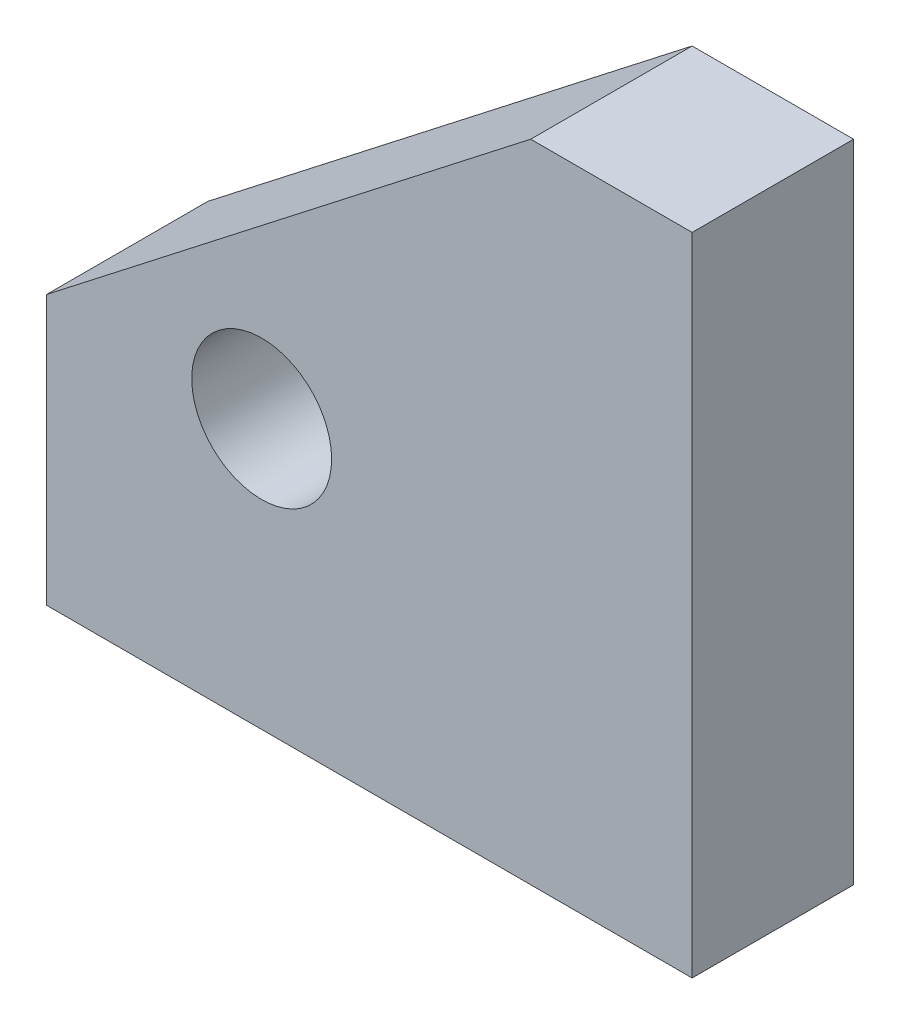
SolidWorks part; units mm, degrees
ref_plane "Front Plane" through (0, 0, 0) normal (1, 0, 0) x (0, 1, 0)
ref_plane "Top Plane" through (0, 0, 0) normal (0, 0, 1) x (0, 1, 0)
ref_plane "Right Plane" through (0, 0, 0) normal (0, 1, 0) x (-1, 0, 0)
sketch "Sketch1" plane through (0, 0, 0) normal (0, 0, 1) x (0, 1, 0)
  line L0 (0, 0) -> (0, 60)
  line L1 (0, 60) -> (60, 60)
  line L2 (60, 60) -> (60, 0)
  line L3 (60, 0) -> (0, 0)
  line L5 (25, 60) -> (60, 15)
  circle A0 centre (25, 40) radius 6.5
  dimension "D3" = 13
  dimension "D1" = 60
  dimension "D2" = 60
  dimension "D4" = 40
  dimension "D6" = 35
  dimension "D7" = 25
  dimension "D8" = 15
extrude "Boss-Extrude2" add sketch "Sketch1" against normal blind 15 contours L5 L1 L0 L3 L2 A0
sketch "Sketch2" plane through (0, 0, 0) normal (1, 0, 0) x (0, 1, 0)
  line L0 (0, 0) -> (0, 45)
  line L1 (0, 45) -> (60, 45)
  line L2 (60, 45) -> (60, 0)
  circle A0 centre (45.1872, 27.2708) radius 7.5
  circle A1 centre (45.1872, 12.2708) radius 7.5
  dimension "D3" = 15
  dimension "D4" = 15
  dimension "D1" = 60
  dimension "D2" = 15
